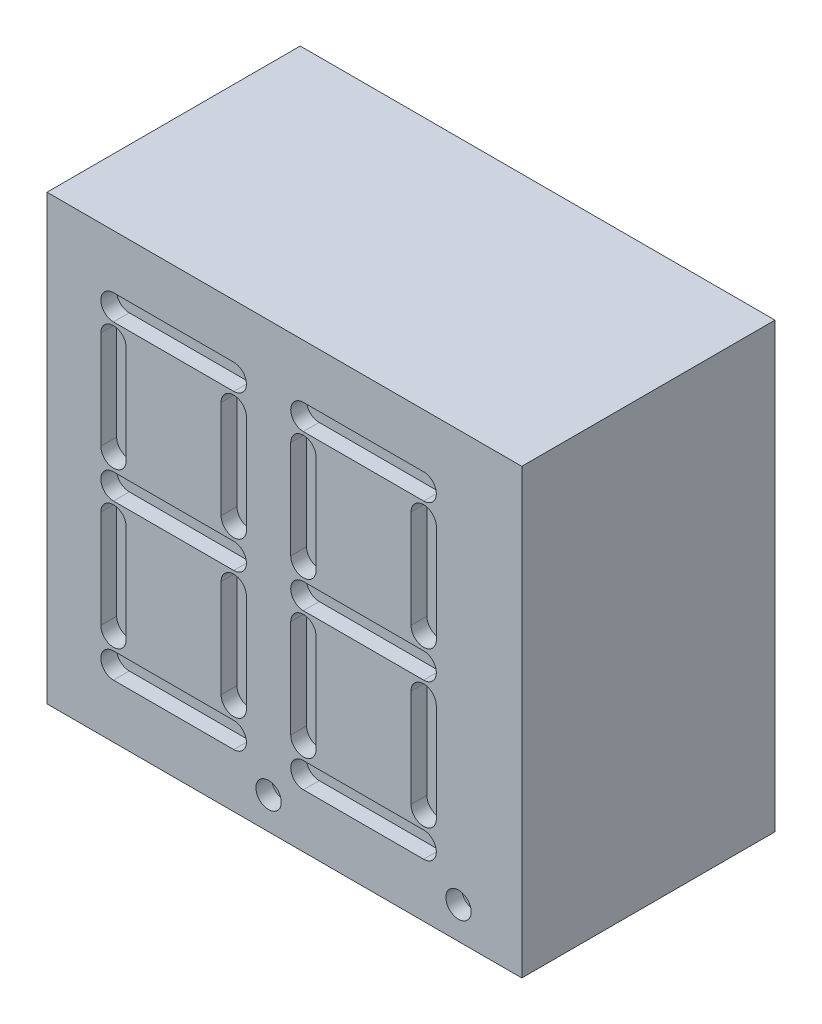
SolidWorks part; units mm, degrees
ref_plane "前视基准面" through (0, 0, 0) normal (0, 0, 1) x (1, 0, 0)
ref_plane "上视基准面" through (0, 0, 0) normal (0, 1, 0) x (1, 0, 0)
ref_plane "右视基准面" through (0, 0, 0) normal (1, 0, 0) x (0, 0, -1)
sketch "草图1" plane through (0, 0, 0) normal (0, 0, 1) x (1, 0, 0)
  line L0 (-1000, 0) -> (49000, 0) construction
  line L1 (0, -1000) -> (0, 49000) construction
  line L2 (-7.5, 7) -> (7.5, 7)
  line L3 (7.5, 7) -> (7.5, -7)
  line L4 (-7.5, 7) -> (-7.5, -7)
  line L5 (-7.5, -7) -> (7.5, -7)
  point P10 (0, 7)
  point P11 (7.5, 0)
  point P12 (-7.5, 0)
  dimension "D1" = 14
  dimension "D2" = 15
extrude "凸台-拉伸1" add sketch "草图1" along normal blind 8
sketch "草图2" plane through (0, 0, 8) normal (0, 0, 1) x (1, 0, 0)
  line L0 (0, 5.5) -> (0, -5.5) construction
  line L1 (7.5, 7) -> (-7.5, 7) construction
  line L3 (6, 0) -> (0, 0) construction
  line L4 (-7.5, 7) -> (-7.5, -7) construction
  line L5 (-6, 5.5) -> (-1, 5.5) construction
  line L7 (-6, -5.5) -> (-1, -5.5) construction
  line L8 (-6, 5.5) -> (-6, -5.5) construction
  line L9 (6, 5.5) -> (6, -5.5) construction
  line L10 (-1, 5.5) -> (-1, -5.5) construction
  line L11 (1, 5.5) -> (1, -5.5) construction
  line L12 (0, 5.5) -> (6, 5.5) construction
  line L13 (-1, 0) -> (-6, 0) construction
  line L14 (0, -5.5) -> (6, -5.5) construction
  line L15 (-3.5, 5.5) -> (-3.5, -5.5) construction
  line L16 (-5.4, 5.3) -> (-1.6, 5.3)
  line L17 (-5.4, 4.5) -> (-1.6, 4.5)
  line L18 (-5.4, -5.3) -> (-1.6, -5.3)
  line L19 (-5.4, -4.5) -> (-1.6, -4.5)
  line L20 (-5.8, 4) -> (-5.8, 0.9)
  line L21 (-5, 4) -> (-5, 0.9)
  line L22 (-2, 4) -> (-2, 0.9)
  line L23 (-1.2, 4) -> (-1.2, 0.9)
  line L24 (-1.2, -4) -> (-1.2, -0.9)
  line L25 (-2, -4) -> (-2, -0.9)
  line L26 (-5.8, -4) -> (-5.8, -0.9)
  line L27 (-5, -4) -> (-5, -0.9)
  line L28 (-5.4, 0.4) -> (-1.6, 0.4)
  line L29 (-5.4, -0.4) -> (-1.6, -0.4)
  line L30 (-1, -5.5) -> (0, -5.5) construction
  line L31 (-0.5, -4.9) -> (-0.5, -6.6397) construction
  line L32 (4.4, -5.3) -> (0.6, -5.3)
  line L33 (4.4, -4.5) -> (0.6, -4.5)
  line L34 (0.2, -4) -> (0.2, -0.9)
  line L35 (1, -4) -> (1, -0.9)
  line L36 (4, -4) -> (4, -0.9)
  line L37 (4.8, -4) -> (4.8, -0.9)
  line L38 (4.4, -0.4) -> (0.6, -0.4)
  line L39 (4.4, 0.4) -> (0.6, 0.4)
  line L40 (0.2, 4) -> (0.2, 0.9)
  line L41 (1, 4) -> (1, 0.9)
  line L42 (4.4, 4.5) -> (0.6, 4.5)
  line L43 (4.4, 5.3) -> (0.6, 5.3)
  line L44 (4, 4) -> (4, 0.9)
  line L45 (4.8, 4) -> (4.8, 0.9)
  arc A0 (-5.4, 5.3) -> (-5.4, 4.5) centre (-5.4, 4.9) ccw
  arc A1 (-1.6, 5.3) -> (-1.6, 4.5) centre (-1.6, 4.9) cw
  arc A2 (-1.6, -5.3) -> (-1.6, -4.5) centre (-1.6, -4.9) ccw
  arc A3 (-5.4, -5.3) -> (-5.4, -4.5) centre (-5.4, -4.9) cw
  arc A4 (-5, 4) -> (-5.8, 4) centre (-5.4, 4) ccw
  arc A5 (-1.2, 0.9) -> (-2, 0.9) centre (-1.6, 0.9) cw
  arc A6 (-5.8, 0.9) -> (-5, 0.9) centre (-5.4, 0.9) ccw
  arc A7 (-5.4, 0.4) -> (-5.4, -0.4) centre (-5.4, 0) ccw
  arc A8 (-2, 4) -> (-1.2, 4) centre (-1.6, 4) cw
  arc A9 (-1.6, 0.4) -> (-1.6, -0.4) centre (-1.6, 0) cw
  arc A10 (-2, -4) -> (-1.2, -4) centre (-1.6, -4) ccw
  arc A11 (-1.2, -0.9) -> (-2, -0.9) centre (-1.6, -0.9) ccw
  arc A12 (-5.8, -0.9) -> (-5, -0.9) centre (-5.4, -0.9) cw
  arc A13 (-5, -4) -> (-5.8, -4) centre (-5.4, -4) cw
  circle A14 centre (-0.5, -5.9922) radius 0.4
  arc A15 (0.6, -5.3) -> (0.6, -4.5) centre (0.6, -4.9) cw
  arc A16 (4.4, -5.3) -> (4.4, -4.5) centre (4.4, -4.9) ccw
  arc A17 (1, -4) -> (0.2, -4) centre (0.6, -4) cw
  arc A18 (4, -4) -> (4.8, -4) centre (4.4, -4) ccw
  arc A19 (0.2, -0.9) -> (1, -0.9) centre (0.6, -0.9) cw
  arc A20 (4.8, -0.9) -> (4, -0.9) centre (4.4, -0.9) ccw
  arc A21 (0.6, 0.4) -> (0.6, -0.4) centre (0.6, 0) ccw
  arc A22 (4.4, 0.4) -> (4.4, -0.4) centre (4.4, 0) cw
  arc A23 (0.2, 0.9) -> (1, 0.9) centre (0.6, 0.9) ccw
  arc A24 (4.8, 0.9) -> (4, 0.9) centre (4.4, 0.9) cw
  arc A25 (1, 4) -> (0.2, 4) centre (0.6, 4) ccw
  arc A26 (4, 4) -> (4.8, 4) centre (4.4, 4) cw
  arc A27 (0.6, 5.3) -> (0.6, 4.5) centre (0.6, 4.9) ccw
  arc A28 (4.4, 5.3) -> (4.4, 4.5) centre (4.4, 4.9) cw
  circle A29 centre (5.5, -5.9922) radius 0.4
  point P12 (0, 0)
  dimension "D4" = 0.8
  dimension "D5" = 0.6
  dimension "D6" = 0.6
  dimension "D7" = 0.8
  dimension "D8" = 0.9
  dimension "D9" = 0.8
  dimension "D10" = 0.9
  dimension "D11" = 1.1
  dimension "D12" = 1.1
  dimension "D1" = 1.5
  dimension "D2" = 1.5
  dimension "D3" = 1
extrude "切除-拉伸1" cut sketch "草图2" against normal blind 0.5
